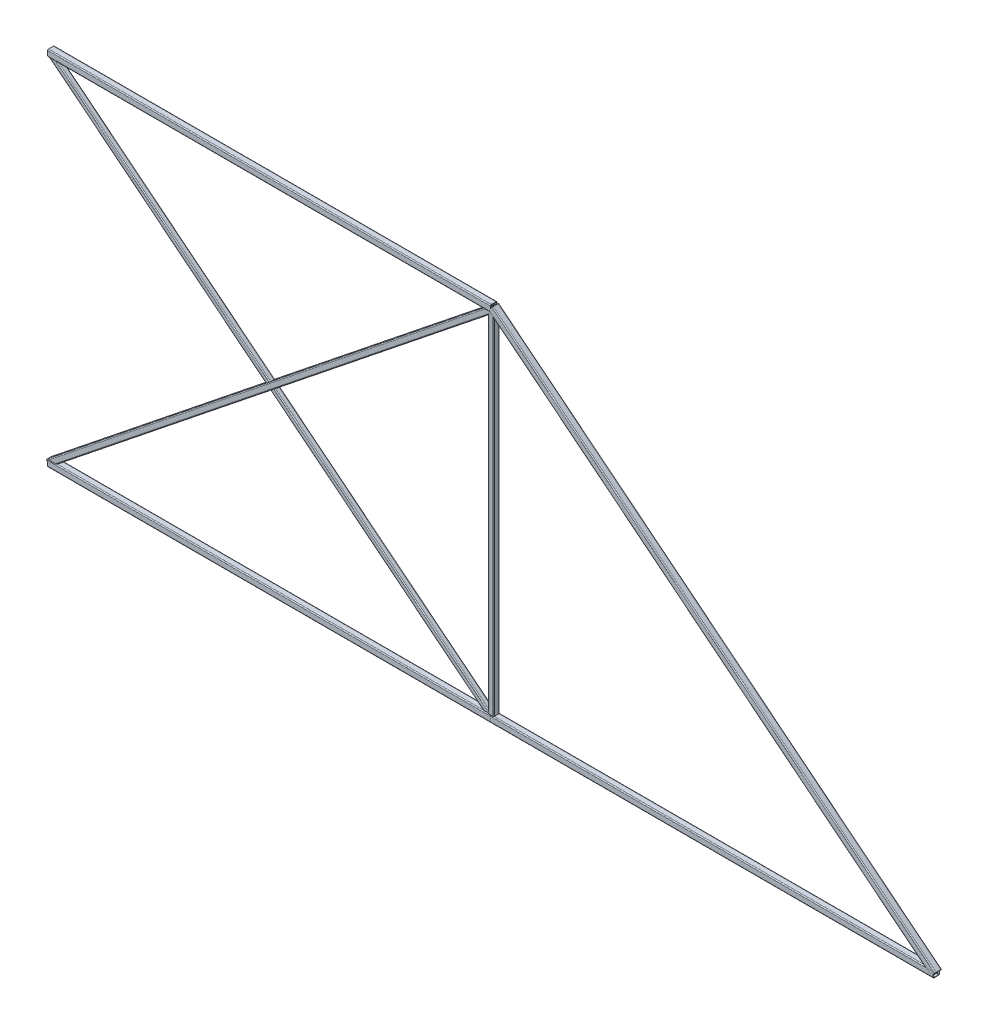
SolidWorks part; units mm, degrees
material "Simulation"
ref_plane "Front Plane" through (0, 0, 0) normal (0, 0, 1) x (1, 0, 0)
ref_plane "Top Plane" through (0, 0, 0) normal (0, 1, 0) x (1, 0, 0)
ref_plane "Right Plane" through (0, 0, 0) normal (1, 0, 0) x (0, 0, -1)
sketch "Sketch1" plane through (0, 0, 0) normal (0, 0, 1) x (1, 0, 0)
  line L0 (0, 0) -> (6096, 0)
  line L1 (0, 4891.6986) -> (6096, 4891.6986)
  line L2 (6096, 4891.6986) -> (12192, 0)
  line L3 (12192, 0) -> (6096, 0)
  line L4 (0, 4891.6986) -> (6096, 0)
  line L5 (6096, 4876.8) -> (6096, 0)
  line L6 (0, 0) -> (6096, 4876.8)
  dimension "D1" = 6096
  dimension "D2" = 6096
  dimension "D3" = 6096
  dimension "D4" = 4876.8
ref_plane "Plane1" through (0, 0, 0) normal (1, 0, 0) x (0, 1, 0)
ref_plane "Plane2" through (0, 0, 0) normal (1, 0, 0) x (0, 1, 0)
other "element 1"
ref_plane "Plane3" through (0, 0, 0) normal (1, 0, 0) x (0, 1, 0)
sketch "Sketch13" plane through (0, 0, 0) normal (1, 0, 0) x (0, 1, 0)
  line L0 (-32.6136, -38.9636) -> (32.6136, -38.9636)
  line L1 (-38.9636, -32.6136) -> (-38.9636, 32.6136)
  line L2 (32.6136, 38.9636) -> (-32.6136, 38.9636)
  line L3 (38.9636, 32.6136) -> (38.9636, -32.6136)
  line L4 (-32.6136, -45.3136) -> (32.6136, -45.3136)
  line L5 (-45.3136, -32.6136) -> (-45.3136, 32.6136)
  line L6 (32.6136, 45.3136) -> (-32.6136, 45.3136)
  line L7 (45.3136, 32.6136) -> (45.3136, -32.6136)
  line L8 (0, 0) -> (38.9636, 0) construction
  line L9 (0, 0) -> (0, 38.9636) construction
  arc A0 (45.3136, 32.6136) -> (32.6136, 45.3136) centre (32.6136, 32.6136) ccw
  arc A1 (32.6136, -45.3136) -> (45.3136, -32.6136) centre (32.6136, -32.6136) ccw
  arc A2 (-45.3136, -32.6136) -> (-32.6136, -45.3136) centre (-32.6136, -32.6136) ccw
  arc A3 (-32.6136, 45.3136) -> (-45.3136, 32.6136) centre (-32.6136, 32.6136) ccw
  arc A4 (-32.6136, 38.9636) -> (-38.9636, 32.6136) centre (-32.6136, 32.6136) ccw
  arc A5 (38.9636, 32.6136) -> (32.6136, 38.9636) centre (32.6136, 32.6136) ccw
  arc A6 (32.6136, -38.9636) -> (38.9636, -32.6136) centre (32.6136, -32.6136) ccw
  arc A7 (-38.9636, -32.6136) -> (-32.6136, -38.9636) centre (-32.6136, -32.6136) ccw
  point P3 (0, 45.3136)
  point P4 (45.3136, 0)
  point P5 (0, -45.3136)
  point P6 (-45.3136, 0)
  point P7 (-45.3136, 45.3136)
  point P8 (-45.3136, -45.3136)
  point P33 (0, 0)
  point P35 (45.3136, -45.3136)
  point P36 (45.3136, 45.3136)
  point P37 (0, 0)
  dimension "D1" = 12.7
  dimension "Thickness" = 6.35
  dimension "V_leg" = 90.6272
other "element 2"
ref_plane "Plane5" through (12192, 0, 0) normal (-1, 0, 0) x (0, -1, 0)
sketch "Sketch15" plane through (12192, 0, 0) normal (-1, 0, 0) x (0, -1, 0)
  line L0 (-32.6136, -38.9636) -> (32.6136, -38.9636)
  line L1 (-38.9636, -32.6136) -> (-38.9636, 32.6136)
  line L2 (32.6136, 38.9636) -> (-32.6136, 38.9636)
  line L3 (38.9636, 32.6136) -> (38.9636, -32.6136)
  line L4 (-32.6136, -45.3136) -> (32.6136, -45.3136)
  line L5 (-45.3136, -32.6136) -> (-45.3136, 32.6136)
  line L6 (32.6136, 45.3136) -> (-32.6136, 45.3136)
  line L7 (45.3136, 32.6136) -> (45.3136, -32.6136)
  line L8 (0, 0) -> (38.9636, 0) construction
  line L9 (0, 0) -> (0, 38.9636) construction
  arc A0 (45.3136, 32.6136) -> (32.6136, 45.3136) centre (32.6136, 32.6136) ccw
  arc A1 (32.6136, -45.3136) -> (45.3136, -32.6136) centre (32.6136, -32.6136) ccw
  arc A2 (-45.3136, -32.6136) -> (-32.6136, -45.3136) centre (-32.6136, -32.6136) ccw
  arc A3 (-32.6136, 45.3136) -> (-45.3136, 32.6136) centre (-32.6136, 32.6136) ccw
  arc A4 (-32.6136, 38.9636) -> (-38.9636, 32.6136) centre (-32.6136, 32.6136) ccw
  arc A5 (38.9636, 32.6136) -> (32.6136, 38.9636) centre (32.6136, 32.6136) ccw
  arc A6 (32.6136, -38.9636) -> (38.9636, -32.6136) centre (32.6136, -32.6136) ccw
  arc A7 (-38.9636, -32.6136) -> (-32.6136, -38.9636) centre (-32.6136, -32.6136) ccw
  point P3 (0, 45.3136)
  point P4 (45.3136, 0)
  point P5 (0, -45.3136)
  point P6 (-45.3136, 0)
  point P7 (-45.3136, 45.3136)
  point P8 (-45.3136, -45.3136)
  point P33 (0, 0)
  point P35 (45.3136, -45.3136)
  point P36 (45.3136, 45.3136)
  point P37 (0, 0)
  dimension "D1" = 12.7
  dimension "Thickness" = 6.35
  dimension "V_leg" = 90.6272
other "element 3"
ref_plane "Plane7" through (0, 4891.6986, 0) normal (1, 0, 0) x (0, 1, 0)
sketch "Sketch17" plane through (0, 4891.6986, 0) normal (1, 0, 0) x (0, 1, 0)
  line L0 (-32.6136, -38.9636) -> (32.6136, -38.9636)
  line L1 (-38.9636, -32.6136) -> (-38.9636, 32.6136)
  line L2 (32.6136, 38.9636) -> (-32.6136, 38.9636)
  line L3 (38.9636, 32.6136) -> (38.9636, -32.6136)
  line L4 (-32.6136, -45.3136) -> (32.6136, -45.3136)
  line L5 (-45.3136, -32.6136) -> (-45.3136, 32.6136)
  line L6 (32.6136, 45.3136) -> (-32.6136, 45.3136)
  line L7 (45.3136, 32.6136) -> (45.3136, -32.6136)
  line L8 (0, 0) -> (38.9636, 0) construction
  line L9 (0, 0) -> (0, 38.9636) construction
  arc A0 (45.3136, 32.6136) -> (32.6136, 45.3136) centre (32.6136, 32.6136) ccw
  arc A1 (32.6136, -45.3136) -> (45.3136, -32.6136) centre (32.6136, -32.6136) ccw
  arc A2 (-45.3136, -32.6136) -> (-32.6136, -45.3136) centre (-32.6136, -32.6136) ccw
  arc A3 (-32.6136, 45.3136) -> (-45.3136, 32.6136) centre (-32.6136, 32.6136) ccw
  arc A4 (-32.6136, 38.9636) -> (-38.9636, 32.6136) centre (-32.6136, 32.6136) ccw
  arc A5 (38.9636, 32.6136) -> (32.6136, 38.9636) centre (32.6136, 32.6136) ccw
  arc A6 (32.6136, -38.9636) -> (38.9636, -32.6136) centre (32.6136, -32.6136) ccw
  arc A7 (-38.9636, -32.6136) -> (-32.6136, -38.9636) centre (-32.6136, -32.6136) ccw
  point P3 (0, 45.3136)
  point P4 (45.3136, 0)
  point P5 (0, -45.3136)
  point P6 (-45.3136, 0)
  point P7 (-45.3136, 45.3136)
  point P8 (-45.3136, -45.3136)
  point P33 (0, 0)
  point P35 (45.3136, -45.3136)
  point P36 (45.3136, 45.3136)
  point P37 (0, 0)
  dimension "D1" = 12.7
  dimension "Thickness" = 6.35
  dimension "V_leg" = 90.6272
other "element 4"
ref_plane "Plane9" through (0, 0, 0) normal (0.7809, 0.6247, 0) x (-0.6247, 0.7809, 0)
sketch "Sketch19" plane through (0, 0, 0) normal (0.7809, 0.6247, 0) x (-0.6247, 0.7809, 0)
  line L0 (-27.8384, -34.1884) -> (27.8384, -34.1884)
  line L1 (-34.1884, -27.8384) -> (-34.1884, 27.8384)
  line L2 (27.8384, 34.1884) -> (-27.8384, 34.1884)
  line L3 (34.1884, 27.8384) -> (34.1884, -27.8384)
  line L4 (-27.8384, -40.5384) -> (27.8384, -40.5384)
  line L5 (-40.5384, -27.8384) -> (-40.5384, 27.8384)
  line L6 (27.8384, 40.5384) -> (-27.8384, 40.5384)
  line L7 (40.5384, 27.8384) -> (40.5384, -27.8384)
  line L8 (0, 0) -> (34.1884, 0) construction
  line L9 (0, 0) -> (0, 34.1884) construction
  arc A0 (40.5384, 27.8384) -> (27.8384, 40.5384) centre (27.8384, 27.8384) ccw
  arc A1 (27.8384, -40.5384) -> (40.5384, -27.8384) centre (27.8384, -27.8384) ccw
  arc A2 (-40.5384, -27.8384) -> (-27.8384, -40.5384) centre (-27.8384, -27.8384) ccw
  arc A3 (-27.8384, 40.5384) -> (-40.5384, 27.8384) centre (-27.8384, 27.8384) ccw
  arc A4 (-27.8384, 34.1884) -> (-34.1884, 27.8384) centre (-27.8384, 27.8384) ccw
  arc A5 (34.1884, 27.8384) -> (27.8384, 34.1884) centre (27.8384, 27.8384) ccw
  arc A6 (27.8384, -34.1884) -> (34.1884, -27.8384) centre (27.8384, -27.8384) ccw
  arc A7 (-34.1884, -27.8384) -> (-27.8384, -34.1884) centre (-27.8384, -27.8384) ccw
  point P3 (0, 40.5384)
  point P4 (40.5384, 0)
  point P5 (0, -40.5384)
  point P6 (-40.5384, 0)
  point P7 (-40.5384, 40.5384)
  point P8 (-40.5384, -40.5384)
  point P33 (0, 0)
  point P35 (40.5384, -40.5384)
  point P36 (40.5384, 40.5384)
  point P37 (0, 0)
  dimension "D1" = 12.7
  dimension "Thickness" = 6.35
  dimension "V_leg" = 81.0768
other "element 5"
ref_plane "Plane8" through (0, 4891.6986, 0) normal (0.7799, -0.6259, 0) x (0.6259, 0.7799, 0)
sketch "Sketch18" plane through (0, 4891.6986, 0) normal (0.7799, -0.6259, 0) x (0.6259, 0.7799, 0)
  line L0 (-22.4028, -28.7528) -> (22.4028, -28.7528)
  line L1 (-28.7528, -22.4028) -> (-28.7528, 22.4028)
  line L2 (22.4028, 28.7528) -> (-22.4028, 28.7528)
  line L3 (28.7528, 22.4028) -> (28.7528, -22.4028)
  line L4 (-22.4028, -35.1028) -> (22.4028, -35.1028)
  line L5 (-35.1028, -22.4028) -> (-35.1028, 22.4028)
  line L6 (22.4028, 35.1028) -> (-22.4028, 35.1028)
  line L7 (35.1028, 22.4028) -> (35.1028, -22.4028)
  line L8 (0, 0) -> (28.7528, 0) construction
  line L9 (0, 0) -> (0, 28.7528) construction
  arc A0 (35.1028, 22.4028) -> (22.4028, 35.1028) centre (22.4028, 22.4028) ccw
  arc A1 (22.4028, -35.1028) -> (35.1028, -22.4028) centre (22.4028, -22.4028) ccw
  arc A2 (-35.1028, -22.4028) -> (-22.4028, -35.1028) centre (-22.4028, -22.4028) ccw
  arc A3 (-22.4028, 35.1028) -> (-35.1028, 22.4028) centre (-22.4028, 22.4028) ccw
  arc A4 (-22.4028, 28.7528) -> (-28.7528, 22.4028) centre (-22.4028, 22.4028) ccw
  arc A5 (28.7528, 22.4028) -> (22.4028, 28.7528) centre (22.4028, 22.4028) ccw
  arc A6 (22.4028, -28.7528) -> (28.7528, -22.4028) centre (22.4028, -22.4028) ccw
  arc A7 (-28.7528, -22.4028) -> (-22.4028, -28.7528) centre (-22.4028, -22.4028) ccw
  point P3 (0, 35.1028)
  point P4 (35.1028, 0)
  point P5 (0, -35.1028)
  point P6 (-35.1028, 0)
  point P7 (-35.1028, 35.1028)
  point P8 (-35.1028, -35.1028)
  point P33 (0, 0)
  point P35 (35.1028, -35.1028)
  point P36 (35.1028, 35.1028)
  point P37 (0, 0)
  dimension "D1" = 12.7
  dimension "Thickness" = 6.35
  dimension "V_leg" = 70.2056
other "element 6"
ref_plane "Plane10" through (6096, 4876.8, 0) normal (0, -1, 0) x (1, 0, 0)
sketch "Sketch110" plane through (6096, 4876.8, 0) normal (0, -1, 0) x (1, 0, 0)
  line L0 (-27.8384, -34.1884) -> (27.8384, -34.1884)
  line L1 (-34.1884, -27.8384) -> (-34.1884, 27.8384)
  line L2 (27.8384, 34.1884) -> (-27.8384, 34.1884)
  line L3 (34.1884, 27.8384) -> (34.1884, -27.8384)
  line L4 (-27.8384, -40.5384) -> (27.8384, -40.5384)
  line L5 (-40.5384, -27.8384) -> (-40.5384, 27.8384)
  line L6 (27.8384, 40.5384) -> (-27.8384, 40.5384)
  line L7 (40.5384, 27.8384) -> (40.5384, -27.8384)
  line L8 (0, 0) -> (34.1884, 0) construction
  line L9 (0, 0) -> (0, 34.1884) construction
  arc A0 (40.5384, 27.8384) -> (27.8384, 40.5384) centre (27.8384, 27.8384) ccw
  arc A1 (27.8384, -40.5384) -> (40.5384, -27.8384) centre (27.8384, -27.8384) ccw
  arc A2 (-40.5384, -27.8384) -> (-27.8384, -40.5384) centre (-27.8384, -27.8384) ccw
  arc A3 (-27.8384, 40.5384) -> (-40.5384, 27.8384) centre (-27.8384, 27.8384) ccw
  arc A4 (-27.8384, 34.1884) -> (-34.1884, 27.8384) centre (-27.8384, 27.8384) ccw
  arc A5 (34.1884, 27.8384) -> (27.8384, 34.1884) centre (27.8384, 27.8384) ccw
  arc A6 (27.8384, -34.1884) -> (34.1884, -27.8384) centre (27.8384, -27.8384) ccw
  arc A7 (-34.1884, -27.8384) -> (-27.8384, -34.1884) centre (-27.8384, -27.8384) ccw
  point P3 (0, 40.5384)
  point P4 (40.5384, 0)
  point P5 (0, -40.5384)
  point P6 (-40.5384, 0)
  point P7 (-40.5384, 40.5384)
  point P8 (-40.5384, -40.5384)
  point P33 (0, 0)
  point P35 (40.5384, -40.5384)
  point P36 (40.5384, 40.5384)
  point P37 (0, 0)
  dimension "D1" = 12.7
  dimension "Thickness" = 6.35
  dimension "V_leg" = 81.0768
other "element 7"
ref_plane "Plane6" through (6096, 4891.6986, 0) normal (0.7799, -0.6259, 0) x (0.6259, 0.7799, 0)
sketch "Sketch16" plane through (6096, 4891.6986, 0) normal (0.7799, -0.6259, 0) x (0.6259, 0.7799, 0)
  line L0 (-32.6136, -38.9636) -> (32.6136, -38.9636)
  line L1 (-38.9636, -32.6136) -> (-38.9636, 32.6136)
  line L2 (32.6136, 38.9636) -> (-32.6136, 38.9636)
  line L3 (38.9636, 32.6136) -> (38.9636, -32.6136)
  line L4 (-32.6136, -45.3136) -> (32.6136, -45.3136)
  line L5 (-45.3136, -32.6136) -> (-45.3136, 32.6136)
  line L6 (32.6136, 45.3136) -> (-32.6136, 45.3136)
  line L7 (45.3136, 32.6136) -> (45.3136, -32.6136)
  line L8 (0, 0) -> (38.9636, 0) construction
  line L9 (0, 0) -> (0, 38.9636) construction
  arc A0 (45.3136, 32.6136) -> (32.6136, 45.3136) centre (32.6136, 32.6136) ccw
  arc A1 (32.6136, -45.3136) -> (45.3136, -32.6136) centre (32.6136, -32.6136) ccw
  arc A2 (-45.3136, -32.6136) -> (-32.6136, -45.3136) centre (-32.6136, -32.6136) ccw
  arc A3 (-32.6136, 45.3136) -> (-45.3136, 32.6136) centre (-32.6136, 32.6136) ccw
  arc A4 (-32.6136, 38.9636) -> (-38.9636, 32.6136) centre (-32.6136, 32.6136) ccw
  arc A5 (38.9636, 32.6136) -> (32.6136, 38.9636) centre (32.6136, 32.6136) ccw
  arc A6 (32.6136, -38.9636) -> (38.9636, -32.6136) centre (32.6136, -32.6136) ccw
  arc A7 (-38.9636, -32.6136) -> (-32.6136, -38.9636) centre (-32.6136, -32.6136) ccw
  point P3 (0, 45.3136)
  point P4 (45.3136, 0)
  point P5 (0, -45.3136)
  point P6 (-45.3136, 0)
  point P7 (-45.3136, 45.3136)
  point P8 (-45.3136, -45.3136)
  point P33 (0, 0)
  point P35 (45.3136, -45.3136)
  point P36 (45.3136, 45.3136)
  point P37 (0, 0)
  dimension "D1" = 12.7
  dimension "Thickness" = 6.35
  dimension "V_leg" = 90.6272
